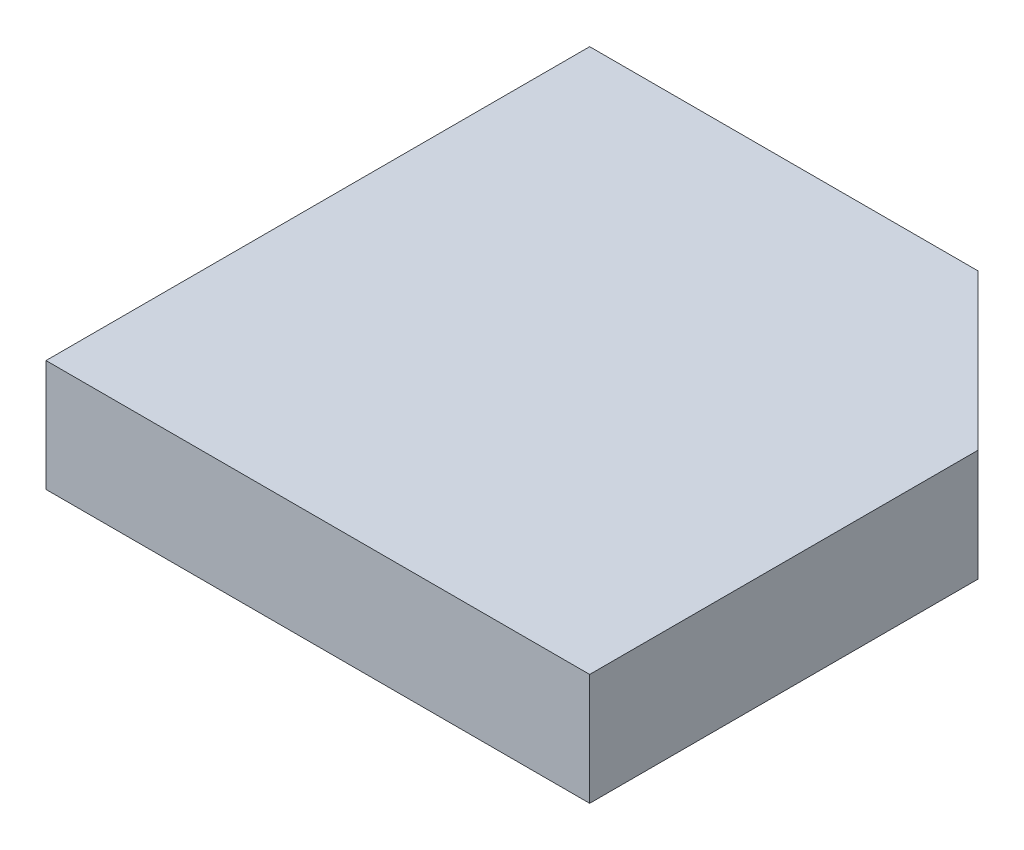
SolidWorks part; units mm, degrees
material "Pine"
ref_plane "Front Plane" through (0, 0, 0) normal (0, 0, 1) x (1, 0, 0)
ref_plane "Top Plane" through (0, 0, 0) normal (0, 1, 0) x (1, 0, 0)
ref_plane "Right Plane" through (0, 0, 0) normal (1, 0, 0) x (0, 0, -1)
sketch "Sketch1" plane through (0, 0, 0) normal (0, 1, 0) x (1, 0, 0)
  line L1 (-44.45, 44.45) -> (44.45, 44.45)
  line L2 (-44.45, 44.45) -> (-44.45, -44.45)
  line L3 (-44.45, -44.45) -> (44.45, -44.45)
  line L4 (44.45, 44.45) -> (44.45, -44.45)
  line L5 (0, -44.45) -> (0, 44.45) construction
  line L6 (-44.45, 0) -> (44.45, 0) construction
  point P0 (0, 0)
  dimension "D1" = 88.9
  dimension "D2" = 88.9
extrude "Boss-Extrude1" add sketch "Sketch1" along normal blind 18.2562
sketch "Sketch2" plane through (0, 18.2562, 0) normal (0, 1, 0) x (1, 0, 0)
  line L1 (44.45, 44.45) -> (44.45, 19.05)
  line L3 (44.45, -44.45) -> (44.45, 44.45) construction
  line L10 (44.45, 19.05) -> (19.05, 44.45)
  line L11 (44.45, 44.45) -> (-44.45, 44.45) construction
  line L12 (19.05, 44.45) -> (44.45, 44.45)
  line L13 (-44.45, -44.45) -> (44.45, -44.45) construction
  dimension "D1" = 63.5
  dimension "D2" = 63.5
extrude "Cut-Extrude1" cut sketch "Sketch2" against normal through all
